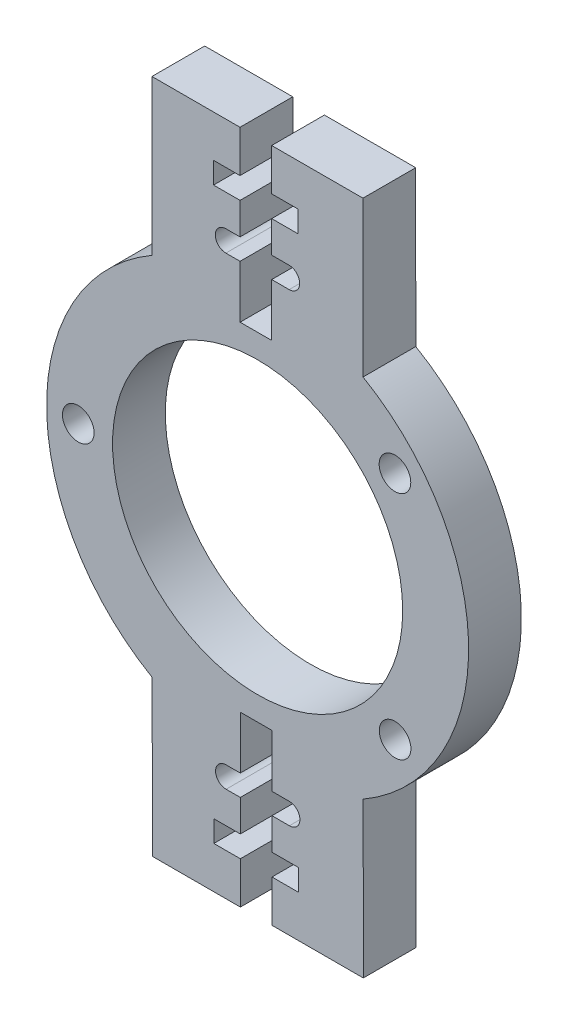
SolidWorks part; units mm, degrees
ref_plane "Front Plane" through (0, 0, 0) normal (0, 0, 1) x (1, 0, 0)
ref_plane "Top Plane" through (0, 0, 0) normal (0, 1, 0) x (1, 0, 0)
ref_plane "Right Plane" through (0, 0, 0) normal (1, 0, 0) x (0, 0, -1)
sketch "Sketch1" plane through (0, 0, 0) normal (0, 0, 1) x (-1, -0.0005, 0)
  line L0 (20, 0) -> (18.5, 0)
  line L1 (-3.8612, -26) -> (-1.3471, -26)
  line L2 (-10, -26) -> (-10, -9.4373)
  line L3 (15.5, 0) -> (13.75, 0)
  line L4 (10, -26) -> (10, -9.4373)
  line L5 (-10, -26) -> (0, 0) construction
  line L6 (-1.3471, -32) -> (-10, -32)
  line L7 (3, -22) -> (-3, -22) construction
  line L8 (4.167, -26) -> (1.6529, -26)
  line L9 (10, -26) -> (10, -32)
  line L10 (10, -32) -> (1.6529, -32)
  line L11 (-10, -26) -> (-10, -32)
  line L12 (-3.8612, -26) -> (-1.3471, -26)
  line L13 (-3.8612, -26) -> (-3.8612, -28.0319)
  line L14 (-3.8612, -28.0319) -> (4.167, -28.0319)
  line L15 (4.167, -26) -> (4.167, -28.0319)
  line L16 (1.6529, -16) -> (-1.3471, -16)
  line L17 (1.6529, -16) -> (1.6529, -21)
  line L18 (1.6529, -26) -> (4.167, -26)
  line L19 (-1.3471, -16) -> (-1.3471, -21)
  line L20 (1.6529, -16) -> (-1.3471, -32) construction
  line L21 (1.6529, -32) -> (-1.3471, -16) construction
  line L22 (3, -23) -> (1.6529, -23)
  line L23 (3, -21) -> (1.6529, -21)
  line L24 (-13.75, 0) -> (-20, 0)
  line L25 (-1.3471, -26) -> (-3.8612, -26)
  line L26 (0, 0) -> (10, -26) construction
  line L27 (1.6529, -26) -> (4.167, -26)
  line L28 (1.6529, -28.0319) -> (1.6529, -32)
  line L29 (-1.3471, -28.0319) -> (-1.3471, -32)
  line L30 (-1.3471, -23) -> (-3, -23)
  line L31 (-1.3471, -23) -> (-1.3471, -26)
  line L32 (-1.3471, -21) -> (-3, -21)
  line L34 (1.6529, -23) -> (1.6529, -26)
  arc A0 (1.6529, -19.9316) -> (20, 0) centre (0, 0) ccw
  arc A2 (15.5, 0) -> (18.5, 0) centre (17, 0) ccw
  circle A3 centre (-13.0228, -10.9274) radius 1.5
  circle A4 centre (2.952, 16.7417) radius 1.5 [skipped]
  arc A7 (3, -23) -> (3, -21) centre (3, -22) ccw
  arc A8 (-3, -21) -> (-3, -23) centre (-3, -22) ccw
  arc A9 (-13.75, 0) -> (13.75, 0) centre (0, 0) ccw
  arc A10 (-17, 0) -> (16.9338, -1.4985) centre (0, 0) ccw construction
  arc A11 (-20, 0) -> (-1.3471, -19.9546) centre (0, 0) ccw
  point P23 (0.1529, -24)
  point P30 (0, -22)
  dimension "D2" = 3
  dimension "D7" = 6
  dimension "D8" = 3
  dimension "D9" = 2
  dimension "D10" = 8
  dimension "D11" = 3
  dimension "D12" = 16
  dimension "D3" = 2
extrude "Boss-Extrude1" add sketch "Sketch1" along normal blind 5
mirror "Mirror1" about plane through (-1.0669, -0.0006, 5) normal (-0.0005, 1, 0) of "Boss-Extrude1"
